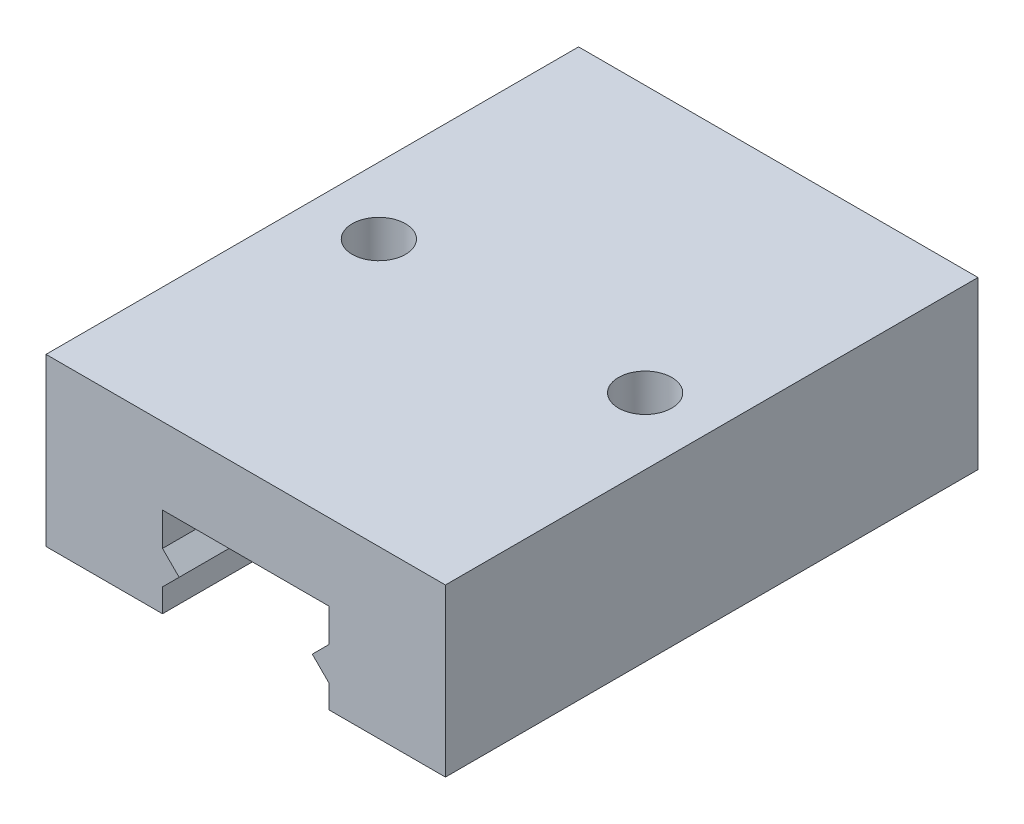
SolidWorks part; units mm, degrees
material "AISI 304"
ref_plane "前视基准面" through (0, 0, 0) normal (0, 0, 1) x (1, 0, 0)
ref_plane "上视基准面" through (0, 0, 0) normal (0, 1, 0) x (1, 0, 0)
ref_plane "右视基准面" through (0, 0, 0) normal (1, 0, 0) x (0, 0, -1)
sketch "Sketch1" plane through (0, 0, 0) normal (0, 0, 1) x (1, 0, 0)
  line L0 (0, 14.151) -> (0, -43.0221) construction
  line L1 (6, 0) -> (-6, 0)
  line L2 (-6, 0) -> (-6, -5)
  line L3 (-6, -5) -> (-2.5, -5)
  line L4 (-2.5, -5) -> (-2.5, -4.3)
  line L5 (-2.5, -4.3) -> (-2, -3.8)
  line L6 (-2, -3.8) -> (-2.5, -3.3)
  line L7 (-2.5, -3.3) -> (-2.5, -2.3)
  line L8 (-2.5, -2.3) -> (2.5, -2.3)
  line L9 (2.5, -3.3) -> (2.5, -2.3)
  line L10 (2, -3.8) -> (2.5, -3.3)
  line L11 (2.5, -5) -> (2.5, -4.3)
  line L12 (2.5, -4.3) -> (2, -3.8)
  line L13 (6, -5) -> (2.5, -5)
  line L14 (6, 0) -> (6, -5)
  point P13 (0, -2.3)
  point P19 (0, 0)
  dimension "D1" = 6
  dimension "D2" = 5
  dimension "D3" = 2.3
  dimension "D4" = 3.5
  dimension "D5" = 2.5
  dimension "D6" = 1
  dimension "D7" = 0.5
  dimension "D8" = 45
extrude "Boss-Extrude1" add sketch "Sketch1" along normal blind 16
sketch "Sketch2" plane through (0, 0, 0) normal (0, 1, 0) x (1, 0, 0)
  line L0 (-6.9114, -8) -> (6.9547, -8) construction
  line L1 (6, 0) -> (-6, 0) construction
  line L2 (-4, 0.9083) -> (-4, -17.6875) construction
  line L3 (-6, -16) -> (-6, 0) construction
  line L4 (0, -1.1019) -> (0, -17.1612) construction
  circle A0 centre (-4, -8) radius 0.8
  circle A1 centre (4, -8) radius 0.8
  dimension "D3" = 1.6
  dimension "D1" = 8
  dimension "D2" = 2
extrude "Cut-Extrude1" cut sketch "Sketch2" against normal blind 16
cosmetic thread "Cosmetic Thread1" parameters "D2"=2
cosmetic thread "Cosmetic Thread2" parameters "D2"=2
